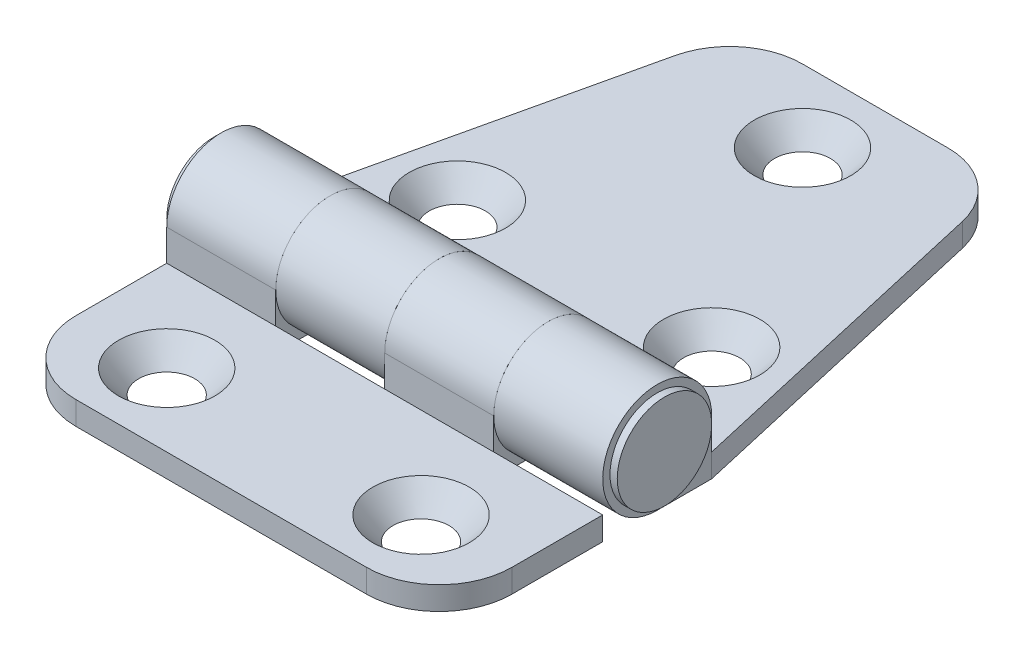
SolidWorks part; units mm, degrees
ref_plane "Front" through (0, 0, 0) normal (0, 0, 1) x (1, 0, 0)
ref_plane "Top" through (0, 0, 0) normal (0, 1, 0) x (1, 0, 0)
ref_plane "Right" through (0, 0, 0) normal (1, 0, 0) x (0, 0, -1)
sketch "Sketch1" plane through (0, 0, 0) normal (1, 0, 0) x (0, 0, -1)
  line L0 (-19.05, -2.7305) -> (-3.902, -2.7305) construction
  line L2 (-4.7625, 0) -> (-4.7625, -2.7305)
  line L3 (0, -4.7625) -> (-19.05, -4.7625)
  line L4 (-19.05, -2.7305) -> (-19.05, -4.7625)
  line L5 (-19.05, -2.7305) -> (-4.7625, -2.7305)
  line L6 (-19.05, -4.7625) -> (38.1, -4.7625) construction
  circle A0 centre (0, 0) radius 2.7781
  arc A2 (-3.902, -2.7305) -> (0, -4.7625) centre (0, 0) cw construction
  arc A3 (0, -4.7625) -> (-4.7625, 0) centre (0, 0) ccw
  dimension "D1" = 9.525
  dimension "Pin Dia" = 5.5562
  dimension "D2" = 19.05
  dimension "Th" = 2.032
  dimension "Open Wd" = 57.15
extrude "Left Leaf" add sketch "Sketch1" along normal mid plane 38.1
sketch "Sketch2" plane through (0, 0, 0) normal (0, 1, 0) x (1, 0, 0)
  line L0 (19.05, -4.7625) -> (-19.05, -4.7625) construction
  line L3 (-19.05, 4.7625) -> (-9.525, 4.7625) construction
  line L4 (-19.05, 4.7625) -> (-19.05, -4.7625) construction
  line L5 (-19.05, -4.7625) -> (-9.525, -4.7625) construction
  line L6 (-19.05, 4.7625) -> (-19.05, -4.7625) construction
  line L7 (9.525, 4.7625) -> (19.05, 4.7625)
  line L8 (-9.525, 4.7625) -> (0, 4.7625)
  line L9 (-9.525, 4.7625) -> (-9.525, -4.7625)
  line L10 (-9.525, -4.7625) -> (0, -4.7625)
  line L11 (9.525, 4.7625) -> (9.525, -4.7625)
  line L12 (0, 4.7625) -> (9.525, 4.7625) construction
  line L13 (19.05, -4.7625) -> (19.05, 4.7625) construction
  line L14 (0, 4.7625) -> (0, -4.7625)
  line L15 (0, -4.7625) -> (9.525, -4.7625) construction
  line L16 (9.525, -4.7625) -> (19.05, -4.7625)
  line L17 (19.05, 4.7625) -> (19.05, -4.7625)
  line L18 (19.05, 4.7625) -> (-19.05, 4.7625) construction
extrude "Cut-Extrude1" cut sketch "Sketch2" against normal through all and the other way through all
sketch "Sketch3" plane through (0, 0, 0) normal (1, 0, 0) x (0, 0, -1)
  line L0 (0, 17.042) -> (0, -15.7543) construction
  line L1 (38.1, -2.7305) -> (38.1, -4.7625)
  line L2 (-19.05, -4.7625) -> (38.1, -4.7625) construction
  line L3 (4.7625, 0) -> (4.7625, -2.7305)
  line L4 (4.7625, -2.7305) -> (38.1, -2.7305)
  line L6 (-19.05, -2.7305) -> (-19.05, -4.7625) construction
  line L19 (0, -4.7625) -> (38.1, -4.7625)
  circle A1 centre (0, 0) radius 2.7781 construction
  arc A4 (4.7625, 0) -> (0, -4.7625) centre (0, 0) ccw
  circle A5 centre (0, 0) radius 2.7781
extrude "Right Leaf" add sketch "Sketch3" along normal mid plane 38.1 separate body
sketch "Sketch9" plane through (0, 0, 0) normal (0, 1, 0) x (1, 0, 0)
  line L1 (0, 4.7625) -> (9.525, 4.7625)
  line L2 (0, 4.7625) -> (0, -4.7625)
  line L3 (0, -4.7625) -> (9.525, -4.7625)
  line L4 (9.525, 4.7625) -> (9.525, -4.7625)
  line L5 (-19.05, 4.7625) -> (-9.525, 4.7625)
  line L6 (-19.05, 4.7625) -> (-19.05, -4.7625)
  line L7 (-19.05, -4.7625) -> (-9.525, -4.7625)
  line L8 (-9.525, 4.7625) -> (-9.525, -4.7625)
extrude "Cut-Extrude2" cut sketch "Sketch9" against normal through all and the other way through all
sketch "Sketch10" plane through (0, 0, 0) normal (1, 0, 0) x (0, 0, -1)
  circle A0 centre (0, 0) radius 2.7781
  circle A1 centre (0, 0) radius 2.7781 construction
extrude "Extrude1" add sketch "Sketch10" along normal mid plane 38.1 separate body
sketch "Sketch13" plane through (0, -2.7305, 0) normal (0, 1, 0) x (-1, 0, 0)
  line L0 (19.05, -4.7625) -> (11.43, -38.1)
  line L3 (-19.05, -38.1) -> (19.05, -38.1) construction
  line L4 (-19.05, -4.7625) -> (-11.43, -38.1)
  line L9 (11.43, -38.1) -> (-11.43, -38.1)
  line L10 (19.05, -4.7625) -> (19.05, -46.9177)
  line L11 (19.05, -46.9177) -> (-19.05, -46.9177)
  line L12 (-19.05, -46.9177) -> (-19.05, -4.7625)
  dimension "D1" = 22.86
extrude "Cut-Extrude3" cut sketch "Sketch13" against normal through all
fillet "Fillet1" radius 6.35 2 edges at (-19.05, -3.7465, 19.05) (19.05, -3.7465, 19.05)
fillet "Fillet2" radius 6.35 2 edges at (11.43, -3.7465, -38.1) (-11.43, -3.7465, -38.1)
sketch "Sketch11" plane through (0, -2.7305, 0) normal (0, 1, 0) x (-1, 0, 0)
  line L0 (-19.05, -4.7625) -> (-19.05, 4.7625) construction
  line L1 (-12.7, 19.05) -> (12.7, 19.05) construction
  line L2 (11.43, -38.1) -> (-11.43, -38.1) construction
  line L6 (0, 19.05) -> (0, -38.1) construction
  line L8 (19.05, 0) -> (-19.05, 0) construction
  line L9 (0, -38.1) -> (0, 19.05) construction
  point P6 (0, -31.75)
  point P7 (11.1125, -12.7)
  point P10 (-11.1125, -12.7)
  point P12 (11.1125, 12.7)
  point P13 (-11.1125, 12.7)
  dimension "D1" = 12.7
  dimension "D2" = 12.7
  dimension "D3" = 22.225
  dimension "D4" = 19.05
hole_wizard "CSK for #8 Flat Head Machine Screw1" positions "3DSketch1" profile "Sketch12" countersink size "#8" standard "Ansi Inch" end condition through all
sketch3d "3DSketch1"
  point P18 (0, -2.7305, -31.75)
  point P22 (-11.1125, -2.7305, -12.7)
  point P25 (11.1125, -2.7305, -12.7)
  point P28 (-11.1125, -2.7305, 12.7)
  point P31 (11.1125, -2.7305, 12.7)
sketch "Sketch12" plane through (0, -2.7305, -31.75) normal (1, 0, 0) x (0, 0, 1)
  line L0 (0, 0) -> (0, 2.032)
  line L1 (0, 2.032) -> (2.2479, 2.032)
  line L2 (2.2479, 2.032) -> (2.2479, 2.2645)
  line L3 (2.2479, 2.2645) -> (4.2164, 0)
  line L5 (4.2164, 0) -> (0, 0)
  line L6 (-2.2479, 2.2645) -> (-4.2164, 0) construction
  line L11 (0, -6.35) -> (0, 107.95) construction
  dimension "Thru Hole Dia." = 4.4958
  dimension "Thru Hole Depth" = 2.032
  dimension "Near C'Sink Dia." = 8.4328
  dimension "Near C'Sink Angle" = 82
ref_plane "Plane1" through (0, 0, 0) normal (0, 1, 0) x (-1, 0, 0)
sketch "Sketch14" plane through (0, 0, 0) normal (0, 1, 0) x (-1, 0, 0)
  line L0 (-9.525, -4.7625) -> (-19.05, -4.7625) construction
  line L1 (-19.05, 0) -> (-19.685, 0)
  line L2 (-19.05, 0) -> (-19.05, -4.1275)
  line L3 (-19.05, -4.1275) -> (-19.685, -4.1275)
  line L5 (-19.685, 0) -> (-19.685, -4.1275)
  line L6 (19.05, 0) -> (19.685, 0)
  line L7 (19.05, 0) -> (19.05, -4.1275)
  line L8 (19.05, -4.1275) -> (19.685, -4.1275)
  line L9 (19.685, 0) -> (19.685, -4.1275)
  line L10 (19.05, 0) -> (-19.05, 0) construction
  dimension "D1" = 0.635
  dimension "D2" = 0.635
revolve "Revolve1" add sketch "Sketch14" angle 360 about L10
